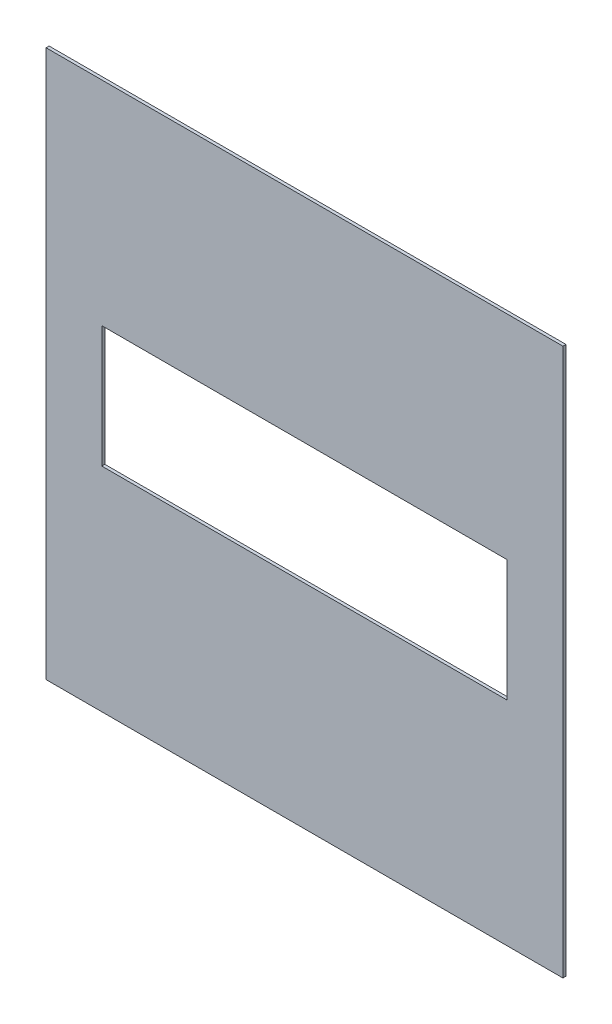
SolidWorks part; units mm, degrees
ref_plane "Front Plane" through (0, 0, 0) normal (0, 0, 1) x (1, 0, 0)
ref_plane "Top Plane" through (0, 0, 0) normal (0, 1, 0) x (1, 0, 0)
ref_plane "Right Plane" through (0, 0, 0) normal (1, 0, 0) x (0, 0, -1)
sketch "Sketch1" plane through (0, 0, 0) normal (0, 0, 1) x (1, 0, 0)
  line L1 (255, 270) -> (-255, 270)
  line L2 (255, 270) -> (255, -270)
  line L3 (255, -270) -> (-255, -270)
  line L4 (-255, 270) -> (-255, -270)
  line L5 (255, 270) -> (-255, -270) construction
  line L6 (255, -270) -> (-255, 270) construction
  point P0 (0, 0)
  dimension "D1" = 540
  dimension "D2" = 510
extrude "Boss-Extrude1" add sketch "Sketch1" along normal blind 3
sketch "Sketch3" plane through (0, 0, 3) normal (0, 0, 1) x (1, 0, 0)
  line L1 (200, -60) -> (-200, -60)
  line L2 (200, -60) -> (200, 60)
  line L3 (200, 60) -> (-200, 60)
  line L4 (-200, -60) -> (-200, 60)
  line L5 (200, -60) -> (-200, 60) construction
  line L6 (200, 60) -> (-200, -60) construction
  point P0 (0, 0)
  dimension "D1" = 120
  dimension "D2" = 400
extrude "Cut-Extrude2" cut sketch "Sketch3" against normal up to next
